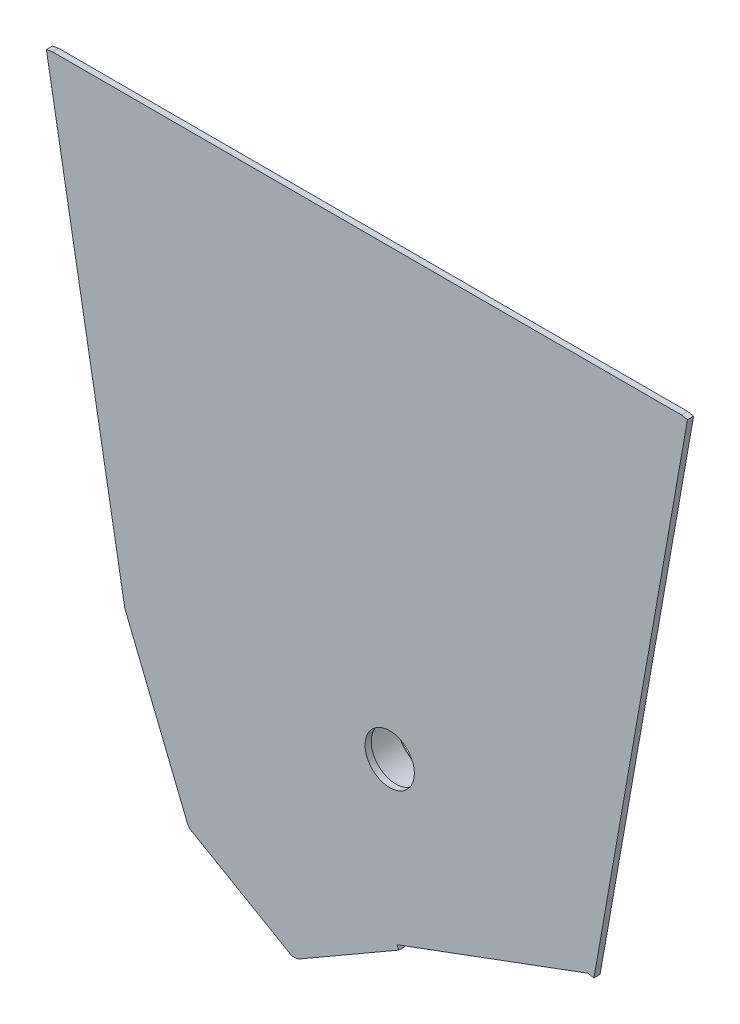
SolidWorks part; units mm, degrees
material "1.0037 (S235JR)"
ref_plane "Płaszczyzna przednia" through (0, 0, 0) normal (0, 0, 1) x (1, 0, 0)
ref_plane "Płaszczyzna górna" through (0, 0, 0) normal (0, 1, 0) x (1, 0, 0)
ref_plane "Płaszczyzna prawa" through (0, 0, 0) normal (1, 0, 0) x (0, 0, -1)
sketch "Szkic1" plane through (0, 0, 0) normal (0, 0, 1) x (1, 0, 0)
  line L0 (184.1034, -161.9156) -> (259.924, 268.0844)
  line L1 (259.924, 268.0844) -> (255, 268.9527)
  line L2 (255, 268.9527) -> (-255, 268.9527)
  line L3 (-255, 268.9527) -> (-259.924, 268.0844)
  line L4 (-259.924, 268.0844) -> (-196.5011, -91.605)
  line L5 (-196.0401, -93.2127) -> (-145.6379, -217.9626)
  line L6 (-142.2204, -221.8939) -> (-62.5686, -267.8809)
  line L7 (-54.5686, -267.8809) -> (25.9777, -221.3774)
  line L8 (25.9777, -221.3774) -> (24.3004, -218.4427)
  line L9 (24.3004, -218.4427) -> (179.1794, -161.0473)
  line L10 (179.1794, -161.0473) -> (184.1034, -161.9156)
  circle A0 centre (18.4777, -91.0473) radius 20
  arc A1 (-196.5011, -91.605) -> (-196.0401, -93.2127) centre (-188.6226, -90.2158) ccw
  arc A2 (-145.6379, -217.9626) -> (-142.2204, -221.8939) centre (-138.2204, -214.9657) ccw
  arc A3 (-62.5686, -267.8809) -> (-54.5686, -267.8809) centre (-58.5686, -260.9527) ccw
  dimension "D1" = 40
extrude "Dodanie-wyciągnięcie1" add sketch "Szkic1" along normal blind 5
sketch "Szkic2" plane through (0, 0, 0) normal (0, 0, -1) x (-1, 0, 0)
  circle A1 centre (-18.4777, -91.0473) radius 30
  circle A2 centre (-18.4777, -91.0473) radius 35
  dimension "D1" = 70
  dimension "D2" = 60
extrude "Dodanie-wyciągnięcie2" add sketch "Szkic2" along normal blind 30
fillet "Zaokrąglenie1" radius 3 2 edges at (-11.5223, -91.0473, 0) (53.4777, -91.0473, 0)
chamfer "Sfazowanie1" distance 1 angle 45 1 edges at (-11.5223, -91.0473, -30)
sketch "Szkic3" plane through (0, 0, -30) normal (0, 0, -1) x (-1, 0, 0)
  line L1 (-38.4777, -75.0473) -> (1.5223, -75.0473)
  line L2 (-38.4777, -75.0473) -> (-38.4777, -45.0473)
  line L3 (-38.4777, -45.0473) -> (1.5223, -45.0473)
  line L4 (1.5223, -75.0473) -> (1.5223, -45.0473)
  line L5 (-38.4777, -75.0473) -> (1.5223, -45.0473) construction
  line L6 (-38.4777, -45.0473) -> (1.5223, -75.0473) construction
  circle A0 centre (-18.4777, -91.0473) radius 31 construction
  point P0 (-18.4777, -60.0473)
  dimension "D1" = 30
  dimension "D2" = 40
extrude "Wytnij-wyciągnięcie1" cut sketch "Szkic3" against normal up to surface (30 mm away) up to face at (56.4777, -91.0473, 0)
